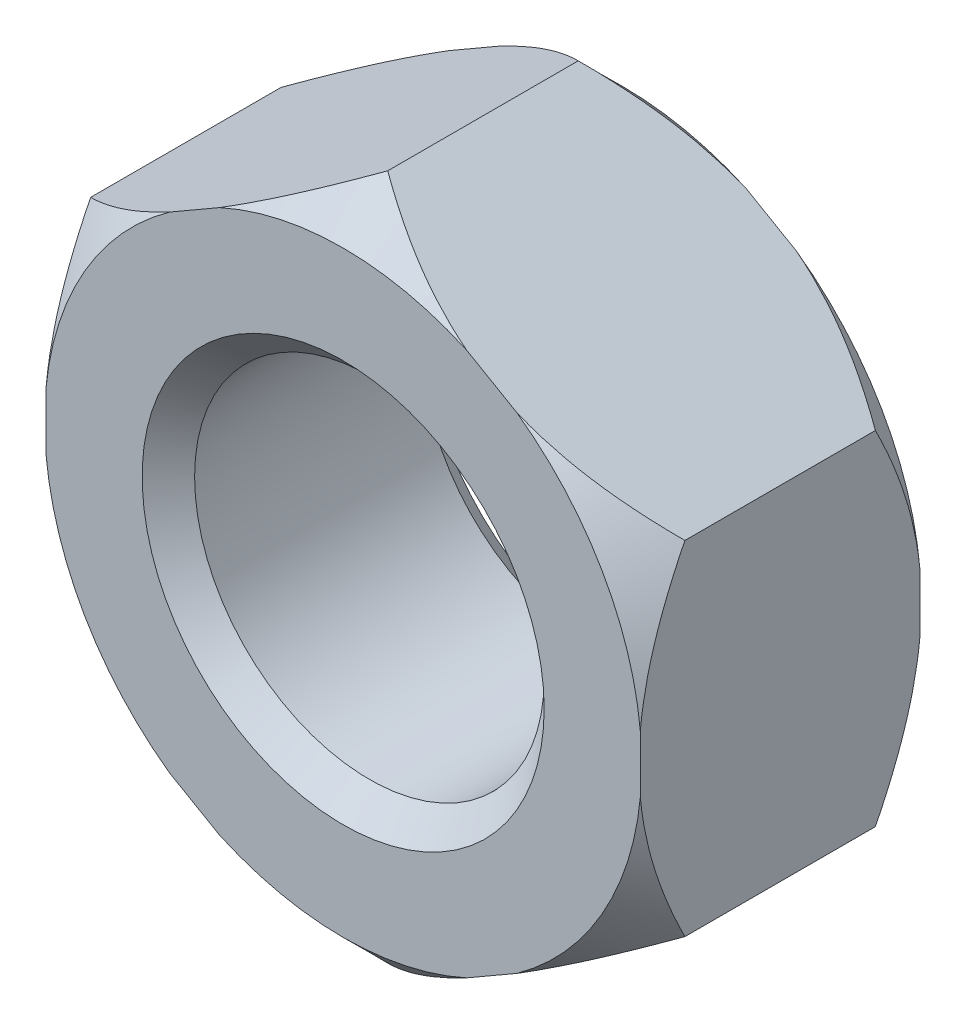
SolidWorks part; units mm, degrees
ref_plane "Спереди" through (0, 0, 0) normal (0, 0, 1) x (1, 0, 0)
ref_plane "Сверху" through (0, 0, 0) normal (0, 1, 0) x (1, 0, 0)
ref_plane "Справа" through (0, 0, 0) normal (1, 0, 0) x (0, 0, -1)
sketch "Эскиз1" plane through (0, 0, 0) normal (0, 0, 1) x (1, 0, 0)
  line L0 (0, 3.7738) -> (0, -4.1898) construction
  line L1 (-3.4469, 0) -> (3.2389, 0) construction
  line L3 (0, 9.815) -> (-8.5, 4.9075)
  line L4 (-8.5, 4.9075) -> (-8.5, -4.9075)
  line L5 (-8.5, -4.9075) -> (0, -9.815)
  line L6 (0, -9.815) -> (8.5, -4.9075)
  line L7 (8.5, -4.9075) -> (8.5, 4.9075)
  line L8 (8.5, 4.9075) -> (0, 9.815)
  circle A0 centre (0, 0) radius 8.5 construction
extrude "Вытянуть1" add sketch "Эскиз1" along normal blind 8
sketch "Эскиз2" plane through (0, 0, 0) normal (0, 0, -1) x (-1, 0, 0)
  circle A0 centre (0, 0) radius 5
ref_axis "Ось4" through (0, 0, 2.6338) along (0, 0, -1)
sketch "Эскиз15" plane through (0, 0, 0) normal (1, 0, 0) x (0, 0, -1)
  line L0 (-8, 9.815) -> (-8, 8.54)
  line L1 (-8, 4.9075) -> (-8, 9.815) construction
  line L2 (-8, 8.54) -> (-6.725, 9.815)
  line L3 (-8, 9.815) -> (0, 9.815) construction
  line L4 (-6.725, 9.815) -> (-8, 9.815)
  line L5 (-1.275, 9.815) -> (0, 9.815)
  line L6 (0, 9.815) -> (0, 8.54)
  line L7 (0, 8.54) -> (-1.275, 9.815)
revolve "Вырез-Повернуть1" cut sketch "Эскиз15" angle 360 about axis through (0, 0, 2.6338) along (0, 0, -1)
ref_plane "Плоскость1" through (8.5, 0.8251, 8) normal (-0.0966, 0.9953, 0) x (-0.9953, -0.0966, 0)
extrude "Вырез-Вытянуть1" cut sketch "Эскиз2" against normal through all
chamfer "Фаска1" distance 0.75 angle 45 2 edges at (-5, 0, 0) (-5, 0, 8)
